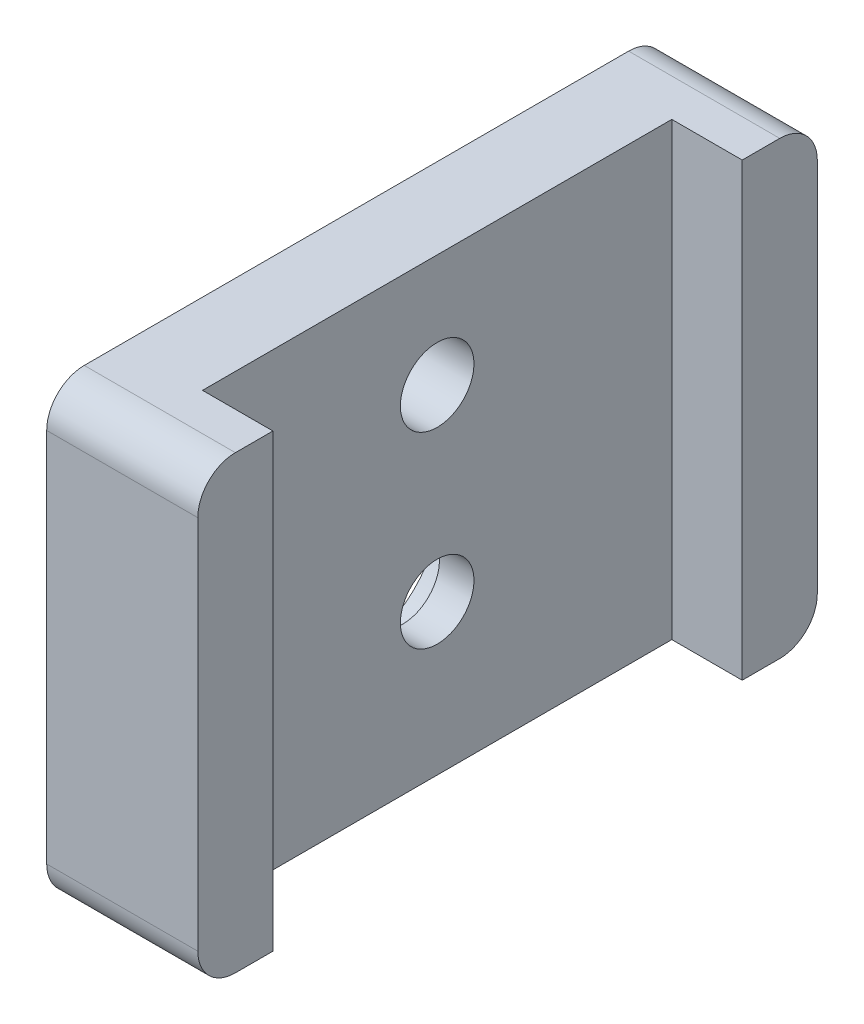
SolidWorks part; units mm, degrees
material "6061-T6 (SS)"
ref_plane "Front Plane" through (0, 0, 0) normal (0, 0, 1) x (1, 0, 0)
ref_plane "Top Plane" through (0, 0, 0) normal (0, 1, 0) x (1, 0, 0)
ref_plane "Right Plane" through (0, 0, 0) normal (1, 0, 0) x (0, 0, -1)
sketch "Sketch1" plane through (0, 0, 0) normal (1, 0, 0) x (0, 0, -1)
  line L0 (0, 15.24) -> (0, 7.62) construction
  line L1 (-15.875, -15.24) -> (15.875, -15.24)
  line L2 (-15.875, -15.24) -> (-15.875, 15.24) construction
  line L3 (-15.875, 15.24) -> (15.875, 15.24)
  line L4 (15.875, -15.24) -> (15.875, 15.24) construction
  line L5 (-15.875, -15.24) -> (15.875, 15.24) construction
  line L6 (-15.875, 15.24) -> (15.875, -15.24) construction
  line L7 (0, 7.62) -> (0, 0) construction
  line L8 (0, 0) -> (0, -5.08) construction
  line L9 (0, -5.08) -> (0, -15.24) construction
  line L10 (-15.875, 15.24) -> (-20.955, 15.24)
  line L11 (-20.955, 15.24) -> (-20.955, -15.24)
  line L12 (-20.955, -15.24) -> (-15.875, -15.24)
  line L13 (15.875, -15.24) -> (20.955, -15.24)
  line L14 (20.955, -15.24) -> (20.955, 15.24)
  line L15 (20.955, 15.24) -> (15.875, 15.24)
  point P0 (0, 0)
  point P8 (0, 7.62)
  point P13 (0, -5.08)
  dimension "D1" = 12.7
  dimension "D2" = 7.62
  dimension "D3" = 31.75
  dimension "D4" = 10.16
  dimension "D5" = 5.08
extrude "Boss-Extrude1" add sketch "Sketch1" along normal blind 5.461
hole_wizard "#10 Clearance Hole1" positions "Sketch6" profile "Sketch5" hole size "#10" standard "ANSI Inch" end condition through all
sketch "Sketch6" plane through (0, 0, 0) normal (-1, 0, 0) x (0, 0, 1)
  point P0 (0, 7.62)
sketch "Sketch5" plane through (0, 7.62, 0) normal (0, 1, 0) x (0, 0, 1)
  line L0 (0, 0) -> (0, 5.461)
  line L1 (0, 5.461) -> (2.4892, 5.461)
  line L2 (2.4892, 5.461) -> (2.4892, 0)
  line L5 (2.4892, 0) -> (0, 0)
  line L11 (0, -6.35) -> (0, 107.95) construction
  dimension "Thru Hole Dia." = 4.9784
  dimension "Thru Hole Depth" = 5.461
hole_wizard "CBORE for #10 Binding Head Machine Screw1" positions "Sketch7" profile "Sketch8" counterbore size "#10" standard "ANSI Inch" end condition through all
sketch "Sketch7" plane through (0, 0, 0) normal (-1, 0, 0) x (0, 0, 1)
  point P0 (0, -5.08)
sketch "Sketch8" plane through (0, -5.08, 0) normal (0, 1, 0) x (0, 0, 1)
  line L0 (0, 0) -> (0, 5.461)
  line L1 (0, 5.461) -> (2.4892, 5.461)
  line L3 (2.4892, 5.461) -> (2.4892, 3.1242)
  line L4 (2.4892, 3.1242) -> (5.5562, 3.1242)
  line L5 (5.5562, 3.1242) -> (5.5562, 0)
  line L7 (5.5562, 0) -> (0, 0)
  line L11 (0, -6.35) -> (0, 107.95) construction
  dimension "Thru Hole Dia." = 4.9784
  dimension "Thru Hole Depth" = 5.461
  dimension "C'Bore Dia." = 11.1125
  dimension "C'Bore Depth" = 3.1242
sketch "Sketch10" plane through (5.461, 0, 0) normal (1, 0, 0) x (0, 0, -1)
  line L1 (-20.955, 15.24) -> (-15.875, 15.24)
  line L2 (-20.955, 15.24) -> (-20.955, -15.24)
  line L3 (-20.955, -15.24) -> (-15.875, -15.24)
  line L4 (-15.875, 15.24) -> (-15.875, -15.24)
  line L5 (-20.955, 15.24) -> (-15.875, -15.24) construction
  line L6 (-20.955, -15.24) -> (-15.875, 15.24) construction
  line L7 (15.875, 15.24) -> (20.955, 15.24)
  line L8 (15.875, 15.24) -> (15.875, -15.24)
  line L9 (15.875, -15.24) -> (20.955, -15.24)
  line L10 (20.955, 15.24) -> (20.955, -15.24)
  line L11 (15.875, 15.24) -> (20.955, -15.24) construction
  line L12 (15.875, -15.24) -> (20.955, 15.24) construction
  point P4 (-18.415, 0)
  point P11 (18.415, 0)
extrude "Boss-Extrude2" add sketch "Sketch10" along normal blind 4.7625
fillet "Fillet2" radius 2.54 4 edges at (5.1117, 15.24, -20.955) (5.1117, -15.24, -20.955) (5.1117, -15.24, 20.955) (5.1117, 15.24, 20.955)
